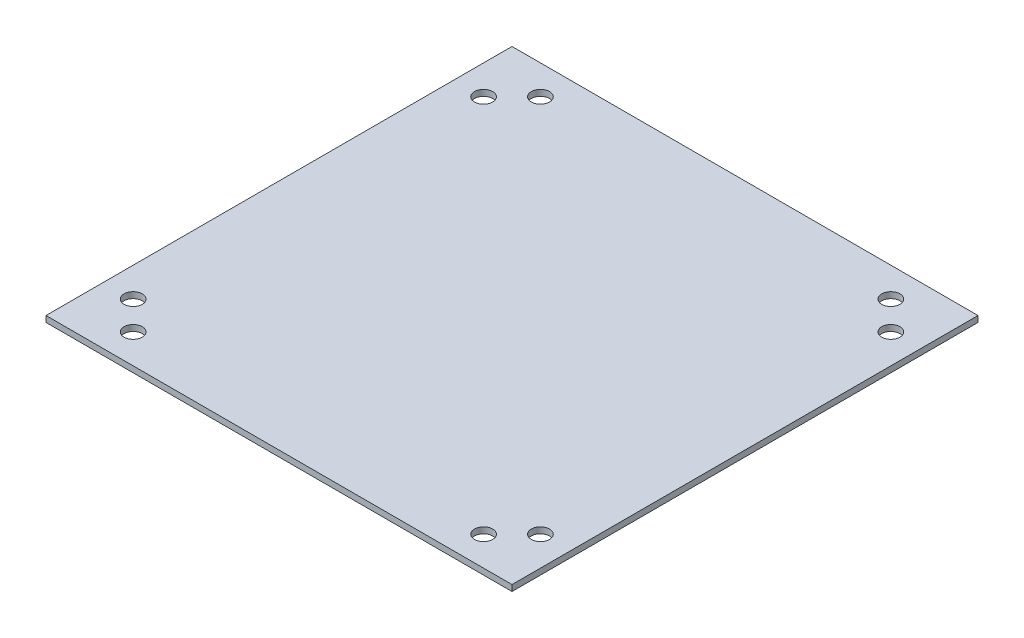
SolidWorks part; units mm, degrees
material "7075-O (SS)"
ref_plane "Front Plane" through (0, 0, 0) normal (0, 0, 1) x (1, 0, 0)
ref_plane "Top Plane" through (0, 0, 0) normal (0, 1, 0) x (1, 0, 0)
ref_plane "Right Plane" through (0, 0, 0) normal (1, 0, 0) x (0, 0, -1)
sketch "Sketch1" plane through (0, 0, 0) normal (0, 1, 0) x (1, 0, 0)
  line L1 (0, 0) -> (97.4, 0)
  line L2 (0, 0) -> (0, 97.4)
  line L3 (0, 97.4) -> (97.4, 97.4)
  line L4 (97.4, 0) -> (97.4, 97.4)
  line L5 (0, 0) -> (7.2, 0)
  line L6 (0, 0) -> (0, 7.2)
  line L7 (0, 7.2) -> (7.2, 7.2)
  line L8 (7.2, 0) -> (7.2, 7.2)
  line L9 (0, 97.4) -> (7.2, 97.4)
  line L10 (0, 97.4) -> (0, 90.2)
  line L11 (0, 90.2) -> (7.2, 90.2)
  line L12 (7.2, 97.4) -> (7.2, 90.2)
  line L13 (97.4, 97.4) -> (90.2, 97.4)
  line L14 (97.4, 97.4) -> (97.4, 90.2)
  line L15 (97.4, 90.2) -> (90.2, 90.2)
  line L16 (90.2, 97.4) -> (90.2, 90.2)
  line L17 (97.4, 0) -> (90.2, 0)
  line L18 (97.4, 0) -> (97.4, 7.2)
  line L19 (97.4, 7.2) -> (90.2, 7.2)
  line L20 (90.2, 0) -> (90.2, 7.2)
  dimension "D1" = 7.2
  dimension "D2" = 7.2
  dimension "D3" = 7.2
  dimension "D4" = 7.2
  dimension "D5" = 97.4
  dimension "D6" = 7.2
  dimension "D7" = 7.2
  dimension "D8" = 97.4
  dimension "D9" = 7.2
  dimension "D10" = 7.2
extrude "Boss-Extrude1" add sketch "Sketch1" along normal blind 1.3 contours L1 L20 L19 L4 L15 L16 L3 L12 L11 L2 L7 L8
sketch "Sketch3" plane through (0, 1.3, 0) normal (0, 1, 0) x (1, 0, 0)
  line L0 (0, 90.2) -> (0, 7.2)
  line L1 (0, 7.2) -> (7.2, 7.2)
  line L2 (7.2, 7.2) -> (7.2, 0)
  line L3 (7.2, 0) -> (7.2, 7.2) construction
  line L4 (7.2, 0) -> (90.2, 0)
  line L5 (90.2, 0) -> (90.2, 7.2)
  line L6 (90.2, 7.2) -> (97.4, 7.2)
  line L7 (97.4, 7.2) -> (97.4, 90.2)
  line L8 (97.4, 90.2) -> (90.2, 90.2)
  line L9 (90.2, 90.2) -> (90.2, 97.4)
  line L10 (90.2, 97.4) -> (7.2, 97.4)
  line L11 (7.2, 97.4) -> (7.2, 90.2)
  line L12 (0, 7.2) -> (0, 90.2) construction
  line L13 (-1.3, 98.7) -> (98.7, 98.7)
  line L14 (-1.3, 98.7) -> (-1.3, -1.3)
  line L15 (-1.3, -1.3) -> (98.7, -1.3)
  line L16 (98.7, 98.7) -> (98.7, -1.3)
  line L17 (7.2, 97.4) -> (90.2, 97.4) construction
  line L18 (97.4, 7.2) -> (97.4, 90.2) construction
  line L19 (7.2, 0) -> (90.2, 0) construction
  line L20 (7.2, 90.2) -> (0, 90.2)
  dimension "D1" = 1.3
  dimension "D2" = 1.3
  dimension "D3" = 1.3
  dimension "D4" = 1.3
extrude "Boss-Extrude3" add sketch "Sketch3" against normal blind 1.3 contours L13 L16 L15 L14
sketch "Sketch2" plane through (0, 0, 0) normal (0, -1, 0) x (1, 0, 0)
  line L0 (7.2, 0) -> (90.2, 0) construction
  line L1 (97.4, -7.2) -> (97.4, -90.2) construction
  line L2 (0, -7.2) -> (0, -90.2) construction
  line L3 (0, -90.2) -> (7.2, -90.2) construction
  line L4 (7.2, -97.4) -> (90.2, -97.4) construction
  line L5 (7.2, -97.4) -> (7.2, -90.2) construction
  line L6 (0, -7.2) -> (7.2, -7.2) construction
  line L7 (90.2, -97.4) -> (90.2, -90.2) construction
  line L8 (97.4, -90.2) -> (90.2, -90.2) construction
  line L9 (7.2, 0) -> (7.2, -7.2) construction
  line L10 (90.2, 0) -> (90.2, -7.2) construction
  line L11 (97.4, -7.2) -> (90.2, -7.2) construction
  circle A0 centre (92.4, -86.3) radius 1.95
  circle A1 centre (86.3, -92.4) radius 1.95
  circle A2 centre (11.1, -92.4) radius 1.95
  circle A3 centre (5, -86.3) radius 1.95
  circle A4 centre (5, -11.1) radius 1.95
  circle A5 centre (11.1, -5) radius 1.95
  circle A6 centre (86.3, -5) radius 1.95
  circle A7 centre (92.4, -11.1) radius 1.95
  dimension "D1" = 3.9
  dimension "D2" = 3.9
  dimension "D3" = 3.9
  dimension "D4" = 3.9
  dimension "D5" = 3.9
  dimension "D6" = 3.9
  dimension "D7" = 3.9
  dimension "D8" = 3.9
  dimension "D9" = 3.9
  dimension "D10" = 3.9
  dimension "D11" = 3.9
  dimension "D12" = 3.9
  dimension "D13" = 5
  dimension "D14" = 5
  dimension "D15" = 5
  dimension "D16" = 5
  dimension "D17" = 5
  dimension "D18" = 5
  dimension "D19" = 3.9
  dimension "D20" = 3.9
  dimension "D21" = 3.9
  dimension "D22" = 5
  dimension "D23" = 5
  dimension "D24" = 3.9
extrude "Cut-Extrude1" cut sketch "Sketch2" against normal blind 1.3
sketch "Sketch4" plane through (0, 0, 0) normal (0, -1, 0) x (1, 0, 0)
  line L0 (3.615, -96.645) -> (3.615, -0.755) construction
  line L1 (3.615, -0.755) -> (93.785, -0.755) construction
  line L2 (93.785, -0.755) -> (93.785, -96.645) construction
  line L3 (93.785, -96.645) -> (3.615, -96.645) construction
  line L4 (-1.3, -98.7) -> (98.7, -98.7) construction
  line L6 (-1.3, -98.7) -> (-1.3, 1.3) construction
  circle A0 centre (12.505, -91.565) radius 1.6
  circle A1 centre (86.165, -91.565) radius 1.6
  circle A2 centre (8.695, -5.835) radius 1.6
  circle A3 centre (88.705, -5.835) radius 1.6
  dimension "D1" = 3.2
  dimension "D2" = 3.2
  dimension "D3" = 3.2
  dimension "D4" = 3.2
  dimension "D5" = 95.89
  dimension "D6" = 90.17
  dimension "D7" = 8.89
  dimension "D8" = 82.55
  dimension "D9" = 90.81
  dimension "D10" = 90.81
  dimension "D11" = 5.08
  dimension "D12" = 5.08
  dimension "D13" = 5.08
  dimension "D14" = 85.09
  dimension "D15" = 2.055
  dimension "D16" = 4.915
